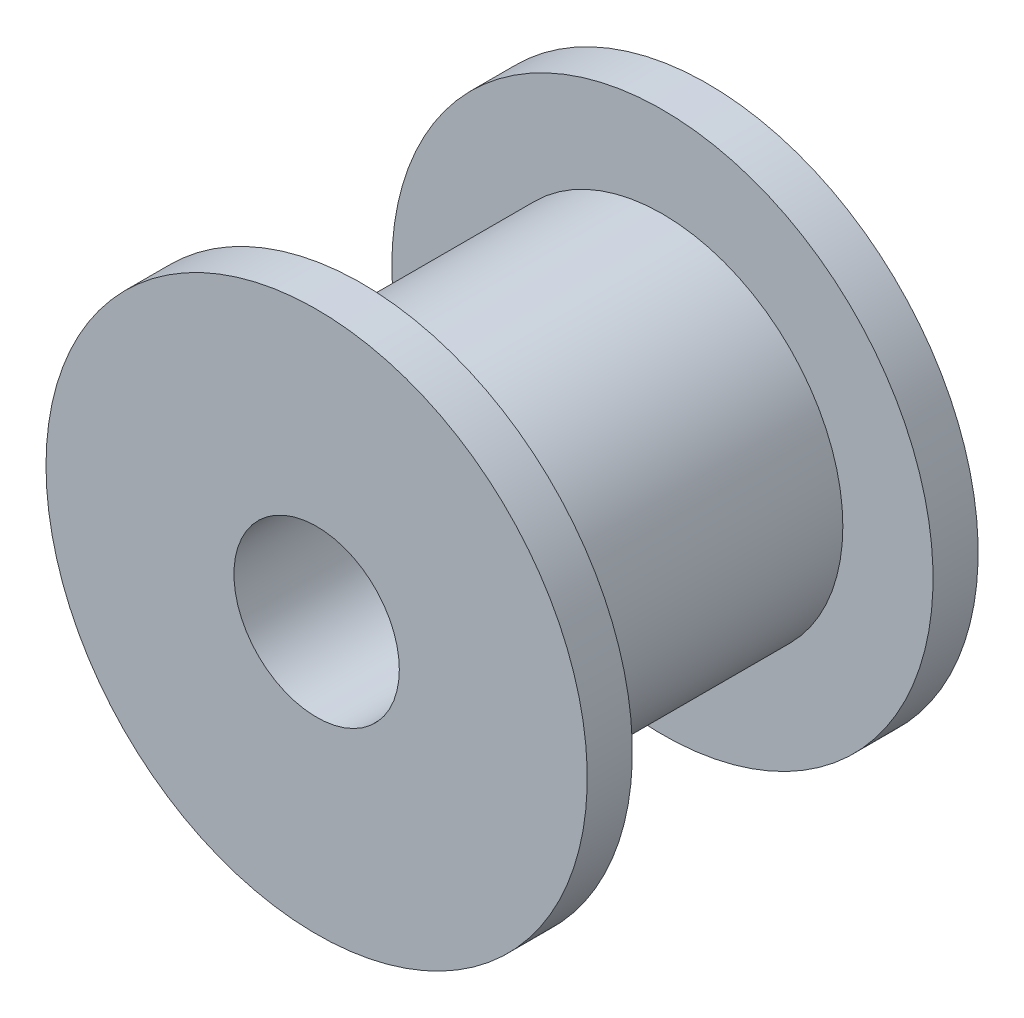
SolidWorks part; units mm, degrees
ref_plane "Front Plane" through (0, 0, 0) normal (0, 0, 1) x (1, 0, 0)
ref_plane "Top Plane" through (0, 0, 0) normal (0, 1, 0) x (1, 0, 0)
ref_plane "Right Plane" through (0, 0, 0) normal (1, 0, 0) x (0, 0, -1)
sketch "Sketch1" plane through (0, 0, 0) normal (0, 0, 1) x (1, 0, 0)
  circle A0 centre (0, 0) radius 9
  dimension "D1" = 18
extrude "Boss-Extrude1" add sketch "Sketch1" along normal mid plane 13
sketch "Sketch2" plane through (0, 0, 0) normal (0, 0, 1) x (1, 0, 0)
  circle A0 centre (0, 0) radius 6
  circle A1 centre (0, 0) radius 9 construction
  circle A2 centre (0, 0) radius 9
  dimension "D1" = 12
extrude "Cut-Extrude2" cut sketch "Sketch2" against normal mid plane 10
sketch "Sketch3" plane through (0, 0, 6.5) normal (0, 0, 1) x (1, 0, 0)
  circle A0 centre (0, 0) radius 2.75
  dimension "D1" = 5.5
extrude "Cut-Extrude3" cut sketch "Sketch3" against normal through all
